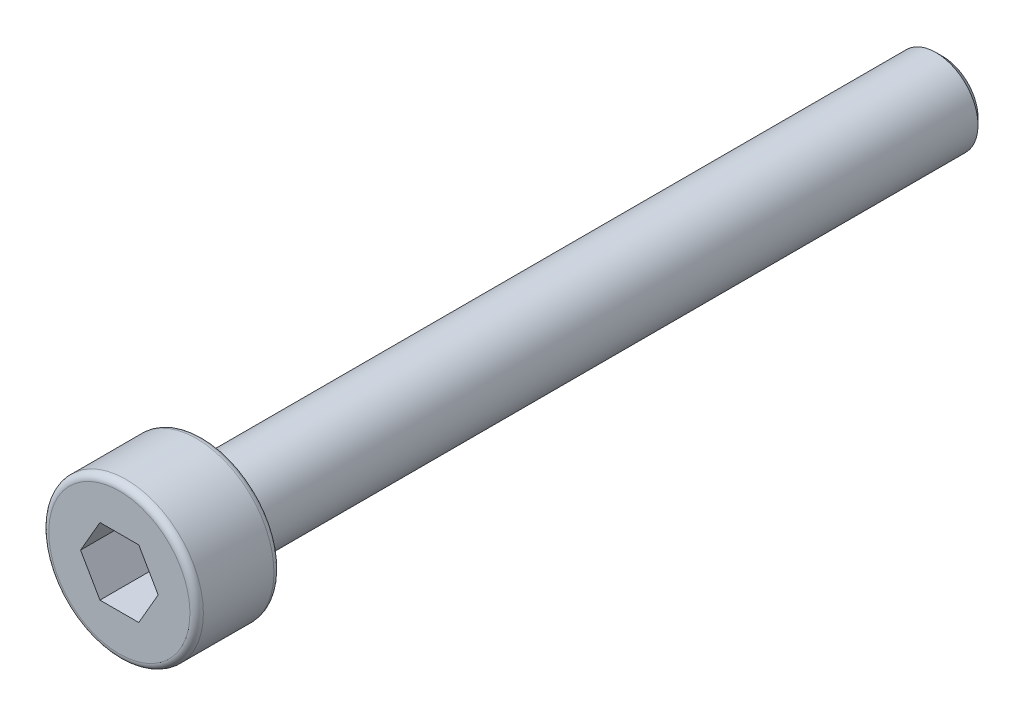
SolidWorks part; units mm, degrees
ref_plane "前视基准面" through (0, 0, 0) normal (0, 0, 1) x (1, 0, 0)
ref_plane "上视基准面" through (0, 0, 0) normal (0, 1, 0) x (1, 0, 0)
ref_plane "右视基准面" through (0, 0, 0) normal (1, 0, 0) x (0, 0, -1)
sketch "草图2" plane through (0, 0, 0) normal (1, 0, 0) x (0, 0, -1)
  line L0 (0, 0) -> (0, 2.3)
  line L1 (0, 2.3) -> (2.5, 2.3)
  line L2 (2.5, 2.3) -> (2.5, 1.25)
  line L3 (2.5, 1.25) -> (24.5, 1.25)
  line L5 (24.5, 1.25) -> (24.5, 0)
  line L6 (24.5, 0) -> (0, 0)
  dimension "D1" = 1.25
  dimension "D2" = 2.3
  dimension "D3" = 2.5
  dimension "D4" = 22
revolve "旋转1" add sketch "草图2" angle 360 about L6
fillet "圆角1" radius 0.2 2 edges at (0, 2.3, -2.5) (0, 2.3, 0)
chamfer "倒角1" distance 0.2 angle 45 1 edges at (0, 1.25, -24.5)
sketch "草图3" plane through (0, 0, 0) normal (0, 0, 1) x (1, 0, 0)
  line L1 (1.1547, 0) -> (0.5774, 1)
  line L2 (0.5774, 1) -> (-0.5774, 1)
  line L3 (-0.5774, 1) -> (-1.1547, 0)
  line L4 (-1.1547, 0) -> (-0.5774, -1)
  line L5 (-0.5774, -1) -> (0.5774, -1)
  line L6 (0.5774, -1) -> (1.1547, 0)
  circle A0 centre (0, 0) radius 1 construction
  dimension "D1" = 2
extrude "切除-拉伸1" cut sketch "草图3" against normal blind 1.5
